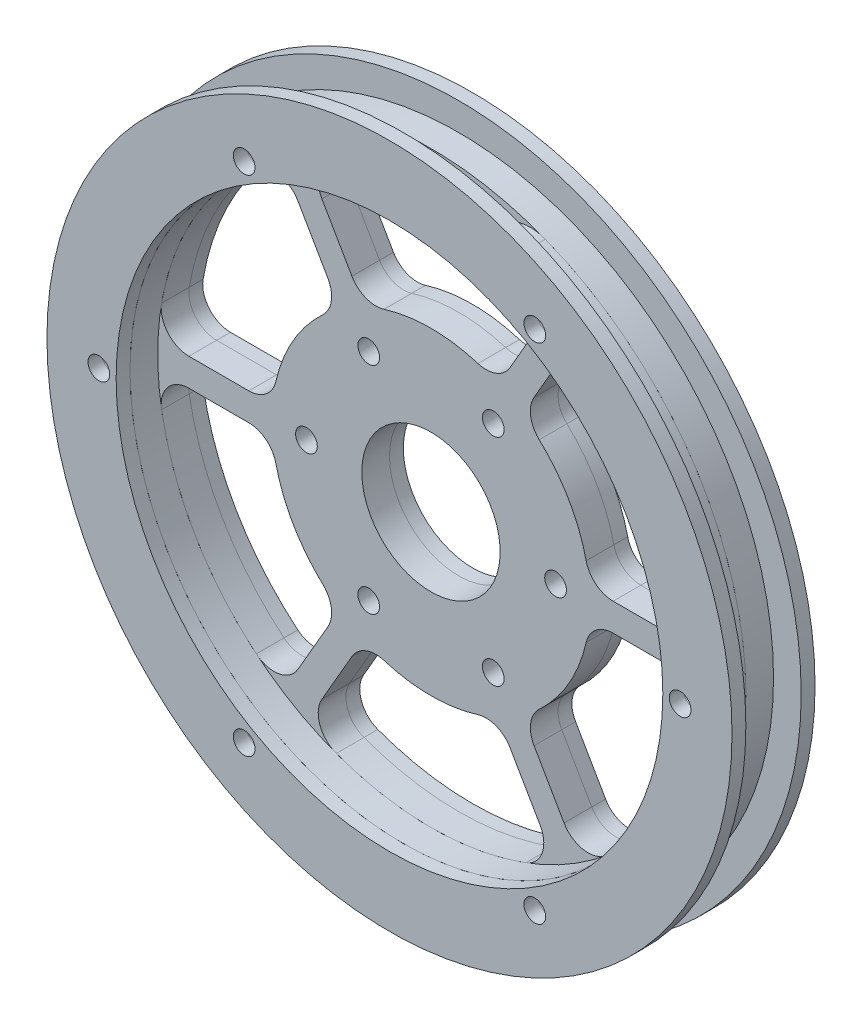
SolidWorks part; units mm, degrees
material "6061-T6 (SS)"
ref_plane "Front Plane" through (0, 0, 0) normal (0, 0, 1) x (1, 0, 0)
ref_plane "Top Plane" through (0, 0, 0) normal (0, 1, 0) x (1, 0, 0)
ref_plane "Right Plane" through (0, 0, 0) normal (1, 0, 0) x (0, 0, -1)
sketch "Sketch1" plane through (0, 0, 0) normal (0, 0, 1) x (1, 0, 0)
  line L0 (0, 0) -> (0, 72.2313) construction
  line L1 (28.575, 0) -> (14.2875, 24.7467) construction
  line L2 (14.2875, 24.7467) -> (-14.2875, 24.7467) construction
  line L3 (-14.2875, 24.7467) -> (-28.575, 0) construction
  line L4 (-28.575, 0) -> (-14.2875, -24.7467) construction
  line L5 (-14.2875, -24.7467) -> (14.2875, -24.7467) construction
  line L6 (14.2875, -24.7467) -> (28.575, 0) construction
  line L7 (28.575, 0) -> (62.7062, 0) construction
  line L8 (14.2875, -24.7467) -> (31.3531, -54.3052) construction
  line L9 (-14.2875, -24.7467) -> (-31.3531, -54.3052) construction
  line L10 (-28.575, 0) -> (-62.7062, 0) construction
  line L11 (-14.2875, 24.7467) -> (-31.3531, 54.3052) construction
  line L12 (-28.575, 3.175) -> (-62.7062, 3.175)
  line L13 (14.2875, 24.7467) -> (31.3531, 54.3052) construction
  line L14 (-11.5379, 26.3342) -> (-28.6035, 55.8927)
  line L15 (17.0371, 23.1592) -> (34.0625, 52.648)
  line L16 (28.575, -3.175) -> (62.6258, -3.175)
  line L17 (11.5379, -26.3342) -> (28.6035, -55.8927)
  line L18 (-17.0371, -23.1592) -> (-34.1028, -52.7177)
  line L19 (-28.575, -3.175) -> (-62.7062, -3.175)
  line L20 (-17.0371, 23.1592) -> (-34.1028, 52.7177)
  line L21 (11.4494, 26.1809) -> (28.5633, 55.823)
  line L22 (28.575, 3.175) -> (62.6258, 3.175)
  line L23 (17.0371, -23.1592) -> (34.1028, -52.7177)
  line L24 (-11.5379, -26.3342) -> (-28.6035, -55.8927)
  line L25 (28.575, 0) -> (62.7062, 0) construction
  line L26 (14.2875, 24.7467) -> (31.3531, 54.3052) construction
  line L27 (17.0371, 23.1592) -> (34.1028, 52.7177) construction
  line L28 (11.5379, 26.3342) -> (28.6035, 55.8927) construction
  line L29 (28.575, 3.175) -> (62.7062, 3.175) construction
  line L30 (28.575, -3.175) -> (62.7062, -3.175) construction
  circle A0 centre (0, 0) radius 72.2313
  circle A1 centre (0, 0) radius 15.875
  circle A2 centre (0, 0) radius 28.575 construction
  circle A3 centre (0, 0) radius 24.7467 construction
  circle A4 centre (28.575, 0) radius 2.4892
  circle A5 centre (14.2875, 24.7467) radius 2.4892
  circle A6 centre (-14.2875, 24.7467) radius 2.4892
  circle A7 centre (-28.575, 0) radius 2.4892
  circle A8 centre (-14.2875, -24.7467) radius 2.4892
  circle A9 centre (14.2875, -24.7467) radius 2.4892
  circle A10 centre (0, 0) radius 36.5125
  arc A11 (62.6258, 3.175) -> (28.5633, 55.823) centre (0, 0) ccw
  arc A12 (28.5633, 55.823) -> (-34.0625, 52.648) centre (0, 0) ccw
  arc A13 (-34.0625, 52.648) -> (-62.6258, -3.175) centre (0, 0) ccw
  arc A14 (-62.6258, -3.175) -> (-28.5633, -55.823) centre (0, 0) ccw
  arc A15 (-28.5633, -55.823) -> (34.0625, -52.648) centre (0, 0) ccw
  arc A16 (34.0625, -52.648) -> (62.6258, 3.175) centre (0, 0) ccw
  arc A17 (26.2344, 67.2987) -> (13.6632, 61.1996) centre (22.7749, 58.4241) ccw
  arc A18 (-26.2344, 67.2987) -> (-13.6632, 61.1996) centre (-22.7749, 58.4241) cw
  circle A19 centre (33.3375, 57.7422) radius 2.4892
  circle A20 centre (-33.3375, 57.7422) radius 2.4892
  circle A21 centre (-66.675, 0) radius 2.4892
  circle A22 centre (-33.3375, -57.7422) radius 2.4892
  circle A23 centre (33.3375, -57.7422) radius 2.4892
  circle A24 centre (66.675, 0) radius 2.4892
  circle A25 centre (0, 0) radius 66.675 construction
  point P44 (11.5379, 26.1421)
  dimension "D1" = 31.75
  dimension "D2" = 144.4625
  dimension "D3" = 57.15
  dimension "D4" = 4.9784
  dimension "D5" = 73.025
  dimension "D6" = 9.525
  dimension "D9" = 133.35
  dimension "D10" = 9.525
  dimension "D7" = 3.175
  dimension "D8" = 3.175
extrude "Boss-Extrude1" add sketch "Sketch1" against normal mid plane 6.35
fillet "Fillet3" radius 1.5875 2 edges at (13.6632, 61.1996, 0) (-13.6632, 61.1996, 0)
sketch "Sketch2" plane through (0, 0, -3.175) normal (0, 0, -1) x (-1, 0, 0)
  line L0 (-11.4494, 26.1809) -> (-28.5633, 55.823) construction
  line L1 (-17.0371, 23.1592) -> (-34.0625, 52.648) construction
  line L2 (11.5379, 26.3342) -> (28.6035, 55.8927) construction
  line L3 (28.575, 3.175) -> (62.7062, 3.175) construction
  line L4 (-17.0371, -23.1592) -> (-34.1028, -52.7177) construction
  line L5 (-28.575, 3.175) -> (-62.6258, 3.175) construction
  line L6 (17.0371, 23.1592) -> (34.1028, 52.7177) construction
  line L7 (28.575, -3.175) -> (62.7062, -3.175) construction
  line L8 (17.0371, -23.1592) -> (34.1028, -52.7177) construction
  line L9 (-11.5379, -26.3342) -> (-28.6035, -55.8927) construction
  line L10 (-28.575, -3.175) -> (-62.6258, -3.175) construction
  line L11 (11.5379, -26.3342) -> (28.6035, -55.8927) construction
  line L12 (-11.4494, 26.1809) -> (-28.5633, 55.823)
  line L13 (-17.0371, 23.1592) -> (-34.0625, 52.648)
  line L14 (11.5379, 26.3342) -> (28.6035, 55.8927)
  line L15 (28.575, 3.175) -> (62.7062, 3.175)
  line L16 (-17.0371, -23.1592) -> (-34.1028, -52.7177)
  line L17 (-28.575, 3.175) -> (-62.6258, 3.175)
  line L18 (17.0371, 23.1592) -> (34.1028, 52.7177)
  line L19 (28.575, -3.175) -> (62.7062, -3.175)
  line L20 (17.0371, -23.1592) -> (34.1028, -52.7177)
  line L21 (-11.5379, -26.3342) -> (-28.6035, -55.8927)
  line L22 (-28.575, -3.175) -> (-62.6258, -3.175)
  line L23 (11.5379, -26.3342) -> (28.6035, -55.8927)
  circle A27 centre (0, 0) radius 72.2313
  arc A32 (-26.2344, 67.2987) -> (26.2344, 67.2987) centre (0, 0) ccw construction
  arc A33 (-28.5633, 55.823) -> (-62.6258, 3.175) centre (0, 0) ccw construction
  circle A34 centre (28.575, 0) radius 2.4892
  circle A35 centre (28.575, 0) radius 2.4892
  circle A36 centre (14.2875, 24.7467) radius 2.4892
  circle A37 centre (14.2875, 24.7467) radius 2.4892
  circle A38 centre (-14.2875, 24.7467) radius 2.4892
  circle A39 centre (-14.2875, 24.7467) radius 2.4892
  circle A40 centre (-28.575, 0) radius 2.4892
  circle A41 centre (-28.575, 0) radius 2.4892
  circle A42 centre (0, 0) radius 15.875
  circle A43 centre (0, 0) radius 15.875
  circle A44 centre (0, 0) radius 72.2313
  circle A45 centre (0, 0) radius 72.2313
  circle A46 centre (0, 0) radius 36.5125
  circle A47 centre (0, 0) radius 36.5125
  circle A48 centre (-14.2875, -24.7467) radius 2.4892
  circle A49 centre (-14.2875, -24.7467) radius 2.4892
  circle A50 centre (14.2875, -24.7467) radius 2.4892
  circle A51 centre (14.2875, -24.7467) radius 2.4892
  circle A52 centre (33.3375, 57.7422) radius 2.4892
  circle A53 centre (33.3375, 57.7422) radius 2.4892
  circle A54 centre (-66.675, 0) radius 2.4892
  circle A55 centre (-66.675, 0) radius 2.4892
  circle A56 centre (-33.3375, -57.7422) radius 2.4892
  circle A57 centre (-33.3375, -57.7422) radius 2.4892
  circle A58 centre (33.3375, -57.7422) radius 2.4892
  circle A59 centre (33.3375, -57.7422) radius 2.4892
  circle A60 centre (66.675, 0) radius 2.4892
  circle A61 centre (66.675, 0) radius 2.4892
  circle A62 centre (-33.3375, 57.7422) radius 2.4892
  circle A63 centre (-33.3375, 57.7422) radius 2.4892
  arc A64 (34.0625, 52.648) -> (-28.5633, 55.823) centre (0, 0) ccw construction
  arc A65 (62.6258, -3.175) -> (34.0625, 52.648) centre (0, 0) ccw construction
  arc A66 (28.5633, -55.823) -> (62.6258, -3.175) centre (0, 0) ccw construction
  arc A67 (-34.0625, -52.648) -> (28.5633, -55.823) centre (0, 0) ccw construction
  arc A68 (-62.6258, 3.175) -> (-34.0625, -52.648) centre (0, 0) ccw construction
  arc A71 (-34.0625, 52.648) -> (-62.6258, 3.175) centre (0, 0) ccw
  arc A72 (28.5633, 55.823) -> (-28.5633, 55.823) centre (0, 0) ccw
  arc A73 (62.6258, -3.175) -> (34.0625, 52.648) centre (0, 0) ccw
  arc A74 (34.0625, -52.648) -> (62.6258, -3.175) centre (0, 0) ccw
  arc A75 (-28.5633, -55.823) -> (28.5633, -55.823) centre (0, 0) ccw
  arc A76 (-62.6258, -3.175) -> (-34.0625, -52.648) centre (0, 0) ccw
  dimension "D1" = 0
  dimension "D3" = 0
  dimension "D4" = 0
  dimension "D2" = 0
  dimension "D5" = 0
  dimension "D6" = 0
  dimension "D7" = 0
  dimension "D8" = 0
  dimension "D9" = 0
  dimension "D10" = 0
  dimension "D11" = 0
  dimension "D12" = 0
  dimension "D13" = 0
  dimension "D14" = 0
  dimension "D15" = 0
extrude "Boss-Extrude2" add sketch "Sketch2" along normal blind 6.35 separate body
sketch "Sketch4" plane through (0, 0, -9.525) normal (0, 0, -1) x (-1, 0, 0)
  line L0 (-11.4494, 26.1809) -> (-28.5633, 55.823) construction
  line L1 (-17.0371, 23.1592) -> (-34.0625, 52.648) construction
  line L2 (11.5379, 26.3342) -> (28.6035, 55.8927) construction
  line L3 (28.575, 3.175) -> (62.7062, 3.175) construction
  line L4 (-17.0371, -23.1592) -> (-34.1028, -52.7177) construction
  line L5 (-28.575, 3.175) -> (-62.6258, 3.175) construction
  line L6 (17.0371, 23.1592) -> (34.1028, 52.7177) construction
  line L7 (28.575, -3.175) -> (62.7062, -3.175) construction
  line L8 (17.0371, -23.1592) -> (34.1028, -52.7177) construction
  line L9 (-11.5379, -26.3342) -> (-28.6035, -55.8927) construction
  line L10 (-28.575, -3.175) -> (-62.6258, -3.175) construction
  line L11 (11.5379, -26.3342) -> (28.6035, -55.8927) construction
  line L12 (-11.4494, 26.1809) -> (-28.5633, 55.823)
  line L13 (-17.0371, 23.1592) -> (-34.0625, 52.648)
  line L14 (11.5379, 26.3342) -> (28.6035, 55.8927)
  line L15 (28.575, 3.175) -> (62.7062, 3.175)
  line L16 (-17.0371, -23.1592) -> (-34.1028, -52.7177)
  line L17 (-28.575, 3.175) -> (-62.6258, 3.175)
  line L18 (17.0371, 23.1592) -> (34.1028, 52.7177)
  line L19 (28.575, -3.175) -> (62.7062, -3.175)
  line L20 (17.0371, -23.1592) -> (34.1028, -52.7177)
  line L21 (-11.5379, -26.3342) -> (-28.6035, -55.8927)
  line L22 (-28.575, -3.175) -> (-62.6258, -3.175)
  line L23 (11.5379, -26.3342) -> (28.6035, -55.8927)
  arc A0 (28.5633, 55.823) -> (-28.5633, 55.823) centre (0, 0) ccw construction
  arc A4 (-15.4615, 60.7702) -> (15.4615, 60.7702) centre (0, 0) ccw construction
  arc A5 (28.5633, 55.823) -> (-28.5633, 55.823) centre (0, 0) ccw
  arc A6 (-15.4615, 60.7702) -> (15.4615, 60.7702) centre (0, 0) ccw
  circle A17 centre (28.575, 0) radius 2.4892
  circle A18 centre (28.575, 0) radius 2.4892
  circle A19 centre (14.2875, 24.7467) radius 2.4892
  circle A20 centre (14.2875, 24.7467) radius 2.4892
  circle A21 centre (-14.2875, 24.7467) radius 2.4892
  circle A22 centre (-14.2875, 24.7467) radius 2.4892
  circle A23 centre (-28.575, 0) radius 2.4892
  circle A24 centre (-28.575, 0) radius 2.4892
  circle A25 centre (0, 0) radius 15.875
  circle A26 centre (0, 0) radius 15.875
  circle A27 centre (0, 0) radius 72.2313
  circle A28 centre (0, 0) radius 72.2313
  circle A29 centre (0, 0) radius 36.5125
  circle A30 centre (0, 0) radius 36.5125
  circle A31 centre (-14.2875, -24.7467) radius 2.4892
  circle A32 centre (-14.2875, -24.7467) radius 2.4892
  circle A33 centre (14.2875, -24.7467) radius 2.4892
  circle A34 centre (14.2875, -24.7467) radius 2.4892
  circle A35 centre (33.3375, 57.7422) radius 2.4892
  circle A36 centre (33.3375, 57.7422) radius 2.4892
  circle A37 centre (-66.675, 0) radius 2.4892
  circle A38 centre (-66.675, 0) radius 2.4892
  circle A39 centre (-33.3375, -57.7422) radius 2.4892
  circle A40 centre (-33.3375, -57.7422) radius 2.4892
  circle A41 centre (33.3375, -57.7422) radius 2.4892
  circle A42 centre (33.3375, -57.7422) radius 2.4892
  circle A43 centre (66.675, 0) radius 2.4892
  circle A44 centre (66.675, 0) radius 2.4892
  circle A45 centre (-33.3375, 57.7422) radius 2.4892
  circle A46 centre (-33.3375, 57.7422) radius 2.4892
  circle A60 centre (0, 0) radius 78.5812
  dimension "D16" = 6.35
  dimension "D1" = 0
  dimension "D2" = 0
  dimension "D3" = 0
  dimension "D4" = 0
  dimension "D5" = 0
  dimension "D6" = 0
  dimension "D7" = 0
  dimension "D8" = 0
  dimension "D9" = 0
  dimension "D10" = 0
  dimension "D11" = 0
  dimension "D12" = 0
  dimension "D13" = 0
  dimension "D14" = 0
  dimension "D15" = 0
extrude "Boss-Extrude3" add sketch "Sketch4" along normal blind 3.175 separate body
sketch "Sketch5" plane through (0, 0, 3.175) normal (0, 0, -1) x (1, 0, 0)
  circle A0 centre (0, 0) radius 62.7062
  arc A1 (15.4615, -60.7702) -> (-15.4615, -60.7702) centre (0, 0) ccw construction
  circle A3 centre (0, 0) radius 78.5812
  circle A4 centre (0, 0) radius 78.5812
  circle A5 centre (33.3375, 57.7422) radius 2.4892 construction
  circle A6 centre (-33.3375, 57.7422) radius 2.4892 construction
  circle A7 centre (-66.675, 0) radius 2.4892 construction
  circle A8 centre (-33.3375, -57.7422) radius 2.4892 construction
  circle A9 centre (33.3375, -57.7422) radius 2.4892 construction
  circle A10 centre (66.675, 0) radius 2.4892 construction
  circle A11 centre (33.3375, 57.7422) radius 2.4892
  circle A12 centre (-33.3375, 57.7422) radius 2.4892
  circle A13 centre (-66.675, 0) radius 2.4892
  circle A14 centre (-33.3375, -57.7422) radius 2.4892
  circle A15 centre (33.3375, -57.7422) radius 2.4892
  circle A16 centre (66.675, 0) radius 2.4892
  dimension "D2" = 0
extrude "Boss-Extrude4" add sketch "Sketch5" against normal blind 3.175 separate body
fillet "Fillet4" radius 6.35 24 edges at (15.4375, 33.0885, -6.35) (-15.4375, 33.0885, -6.35) (-28.5633, 55.823, -6.35) (28.5633, 55.823, -6.35) (-62.6258, 3.175, -6.35) (-34.0625, 52.648, -6.35) (-20.9367, 29.9135, -6.35) (-36.3742, 3.175, -6.35) (-34.0625, -52.648, -6.35) (-62.6258, -3.175, -6.35) (-36.3742, -3.175, -6.35) (-20.9367, -29.9135, -6.35) (28.5633, -55.823, -6.35) (-28.5633, -55.823, -6.35) (-15.4375, -33.0885, -6.35) (15.4375, -33.0885, -6.35) (62.6258, -3.175, -6.35) (34.0625, -52.648, -6.35) (20.9367, -29.9135, -6.35) (36.3742, -3.175, -6.35) (34.0625, 52.648, -6.35) (62.6258, 3.175, -6.35) (36.3742, 3.175, -6.35) (20.9367, 29.9135, -6.35)
fillet "Fillet5" radius 6.35 24 edges at (-36.3742, 3.175, -11.1125) (-62.6258, 3.175, -11.1125) (-34.0625, 52.648, -11.1125) (-20.9367, 29.9135, -11.1125) (28.5633, 55.823, -11.1125) (15.4375, 33.0885, -11.1125) (-15.4375, 33.0885, -11.1125) (-28.5633, 55.823, -11.1125) (62.6258, 3.175, -11.1125) (36.3742, 3.175, -11.1125) (20.9367, 29.9135, -11.1125) (34.0625, 52.648, -11.1125) (34.0625, -52.648, -11.1125) (20.9367, -29.9135, -11.1125) (36.3742, -3.175, -11.1125) (62.6258, -3.175, -11.1125) (-28.5633, -55.823, -11.1125) (-15.4375, -33.0885, -11.1125) (15.4375, -33.0885, -11.1125) (28.5633, -55.823, -11.1125) (-62.6258, -3.175, -11.1125) (-36.3742, -3.175, -11.1125) (-20.9367, -29.9135, -11.1125) (-34.0625, -52.648, -11.1125)
